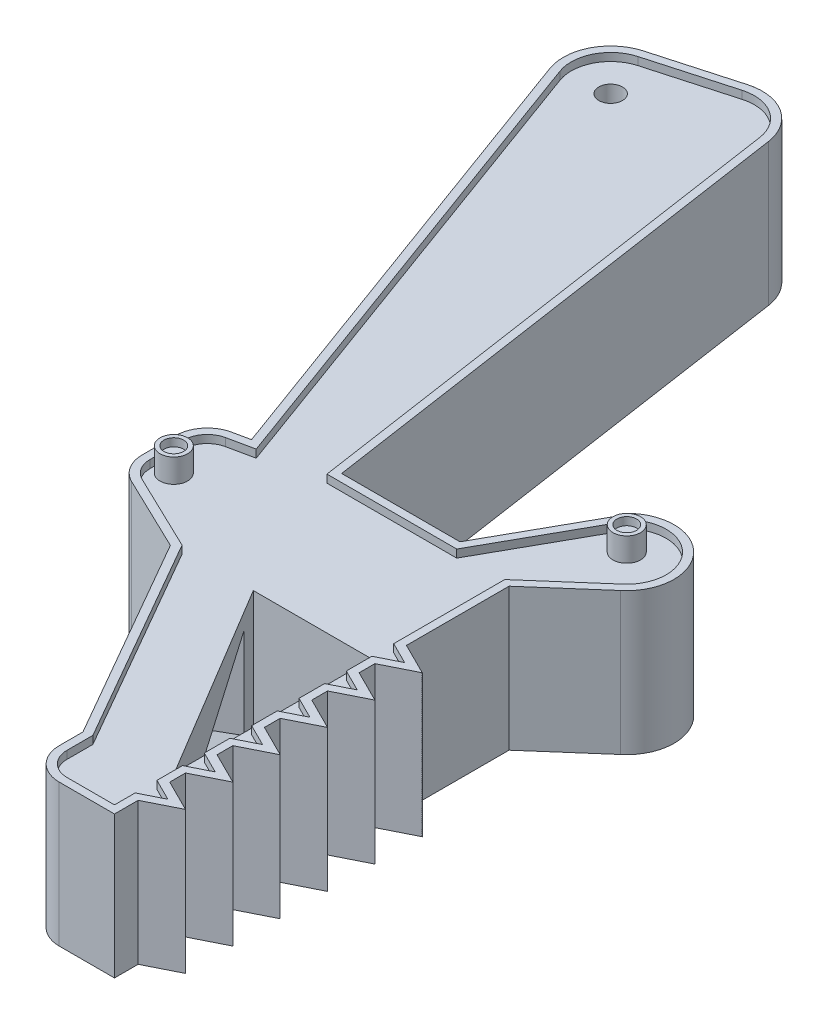
SolidWorks part; units mm, degrees
ref_plane "Front Plane" through (0, 0, 0) normal (0, 0, 1) x (1, 0, 0)
ref_plane "Top Plane" through (0, 0, 0) normal (0, 1, 0) x (1, 0, 0)
ref_plane "Right Plane" through (0, 0, 0) normal (1, 0, 0) x (0, 0, -1)
sketch "Sketch1" plane through (0, 0, 0) normal (0, 1, 0) x (1, 0, 0)
  line L0 (0, 0) -> (-94.594, 0) construction
  line L1 (-36.5878, -72.2334) -> (-60.6545, -6.5006)
  line L2 (-60.6545, -6.5006) -> (-37.5516, 0)
  line L3 (-37.5516, 0) -> (-27.1663, -70.2363)
  line L5 (-27.1663, -70.2363) -> (-41.8402, -73.3468)
  line L6 (-41.8402, -73.3468) -> (-41.8402, -83.3468)
  line L7 (-41.8402, -83.3468) -> (-30.1245, -88.9808)
  line L8 (-30.1245, -88.9808) -> (-15.1886, -114.9984)
  line L9 (-15.1886, -114.9984) -> (-15.1886, -121.9984)
  line L10 (-15.1886, -121.9984) -> (-4.1886, -121.9984)
  line L11 (-4.1886, -121.9984) -> (-4.1886, -71.9984)
  line L12 (-4.1886, -71.9984) -> (3.339, -65.4154)
  line L13 (-27.1663, -70.2363) -> (-12.169, -70.2363)
  line L14 (-12.169, -70.2363) -> (-4.3051, -56.1651)
  arc A0 (-4.3051, -56.1651) -> (3.339, -65.4154) centre (-0.483, -60.7902) cw
  dimension "D12" = 6
  dimension "D1" = 70
  dimension "D2" = 71
  dimension "D3" = 24
  dimension "D4" = 15
  dimension "D5" = 10
  dimension "D6" = 13
  dimension "D7" = 30
  dimension "D8" = 7
  dimension "D9" = 11
  dimension "D10" = 50
  dimension "D11" = 10
extrude "Boss-Extrude1" add sketch "Sketch1" along normal mid plane 18 contours L5 L3 L2 L1 | A0 L14 L13 L5 L6 L7 L8 L9 L10 L11 L12
fillet "Fillet1" radius 6 2 edges at (-37.5516, 0, 0) (-60.6545, 0, 6.5006)
fillet "Fillet2" radius 4 3 edges at (-15.1886, 0, 121.9984) (-41.8402, 0, 83.3468) (-41.8402, 0, 73.3468)
sketch "Sketch2" plane through (0, 9, 0) normal (0, 1, 0) x (1, 0, 0)
  line L0 (-4.1886, -121.9984) -> (-4.1886, -116.9984)
  line L1 (-4.1886, -121.9984) -> (-4.1886, -71.9984) construction
  line L2 (-4.1886, -116.9984) -> (-0.1886, -116.9984) construction
  line L3 (-4.1886, -114.9984) -> (-4.1886, -118.9984)
  line L4 (-4.1886, -114.9984) -> (-0.1886, -116.9984)
  line L5 (-0.1886, -116.9984) -> (-4.1886, -118.9984)
  point P9 (-4.1886, -116.9984)
  dimension "D1" = 5
  dimension "D2" = 4
  dimension "D3" = 4
extrude "Boss-Extrude2" add sketch "Sketch2" against normal blind 18 contours L4 L5 L3
pattern_linear "LPattern1" count 6 spacing 6 along (0, 0, -1) of "Boss-Extrude2"
sketch "Sketch3" plane through (0, 9, 0) normal (0, 1, 0) x (1, 0, 0)
  line L0 (-5.9101, -112.6819) -> (-5.9101, -87.6819)
  line L1 (-5.9101, -87.6819) -> (-20.9101, -87.6819)
  line L2 (-20.9101, -87.6819) -> (-5.9101, -112.6819)
  dimension "D1" = 15
  dimension "D2" = 25
extrude "Cut-Extrude1" cut sketch "Sketch3" against normal blind 26
sketch "Sketch5" plane through (-61.0774, 0, 35.0628) normal (-0.8673, 0, 0.4979) x (0.4979, 0, 0.8673)
  line L0 (68.9983, 6) -> (68.9983, -5.6071)
  line L1 (68.9983, -5.6071) -> (87.171, -0.9465)
  line L2 (87.171, -0.9465) -> (87.171, 1.3394)
  line L3 (87.171, 1.3394) -> (68.9983, 6)
  line L6 (62.171, 9) -> (92.171, 9) construction
  line L7 (92.171, 9) -> (92.171, -9) construction
  point P5 (68.9983, 0.1965)
  point P8 (87.171, 0.1965)
  dimension "D1" = 3
  dimension "D2" = 5
extrude "Cut-Extrude2" cut sketch "Sketch5" against normal blind 12
sketch "Sketch6" plane through (0, 9, 0) normal (0, 1, 0) x (1, 0, 0)
  circle A0 centre (-52.7928, -10.5215) radius 1.5
  dimension "D1" = 3
extrude "Cut-Extrude3" cut sketch "Sketch6" against normal through all
sketch "Sketch7" plane through (0, 9, 0) normal (0, 1, 0) x (1, 0, 0)
  circle A0 centre (-37.8402, -80.8319) radius 1.75
  circle A1 centre (-0.483, -60.7902) radius 1.75
  dimension "D1" = 3.5
  dimension "D2" = 3.5
extrude "Boss-Extrude3" add sketch "Sketch7" along normal blind 3
sketch "Sketch8" plane through (0, 12, 0) normal (0, 1, 0) x (1, 0, 0)
  circle A2 centre (-37.8402, -80.8319) radius 1.25
  circle A3 centre (-37.8402, -80.8319) radius 1.25
  dimension "D1" = 0.5
extrude "Cut-Extrude4" cut sketch "Sketch8" against normal blind 1
sketch "Sketch9" plane through (0, 12, 0) normal (0, 1, 0) x (1, 0, 0)
  circle A3 centre (-0.483, -60.7902) radius 1.25
  circle A4 centre (-0.483, -60.7902) radius 1.25
  dimension "D1" = 0.5
extrude "Cut-Extrude5" cut sketch "Sketch9" against normal blind 1
sketch "Sketch10" plane through (0, 9, 0) normal (0, 1, 0) x (1, 0, 0)
  line L62 (-14.1886, -114.7318) -> (-14.1886, -117.9984)
  line L63 (-11.1886, -120.9984) -> (-5.1886, -120.9984)
  line L64 (-5.1886, -120.9984) -> (-5.1886, -118.3804)
  line L65 (-5.1886, -118.3804) -> (-2.4246, -116.9984)
  line L66 (-2.4246, -116.9984) -> (-5.1886, -115.6165)
  line L67 (-5.1886, -115.6165) -> (-5.1886, -112.3804)
  line L68 (-5.1886, -112.3804) -> (-2.4246, -110.9984)
  line L69 (-2.4246, -110.9984) -> (-5.1886, -109.6165)
  line L70 (-5.1886, -109.6165) -> (-5.1886, -106.3804)
  line L71 (-5.1886, -106.3804) -> (-2.4246, -104.9984)
  line L72 (-2.4246, -104.9984) -> (-5.1886, -103.6165)
  line L73 (-5.1886, -103.6165) -> (-5.1886, -100.3804)
  line L74 (-5.1886, -100.3804) -> (-2.4246, -98.9984)
  line L75 (-2.4246, -98.9984) -> (-5.1886, -97.6165)
  line L76 (-5.1886, -97.6165) -> (-5.1886, -94.3804)
  line L77 (-5.1886, -94.3804) -> (-2.4246, -92.9984)
  line L78 (-2.4246, -92.9984) -> (-5.1886, -91.6165)
  line L79 (-5.1886, -91.6165) -> (-5.1886, -88.3804)
  line L80 (-5.1886, -88.3804) -> (-2.4246, -86.9984)
  line L81 (-2.4246, -86.9984) -> (-5.1886, -85.6165)
  line L82 (-5.1886, -85.6165) -> (-5.1886, -71.5445)
  line L83 (-5.1886, -71.5445) -> (2.6917, -64.653)
  line L84 (-3.5279, -56.8243) -> (-11.5823, -71.2363)
  line L85 (-11.5823, -71.2363) -> (-28.0293, -71.2363)
  line L86 (-28.0293, -71.2363) -> (-37.5435, -6.8911)
  line L87 (-43.8441, -2.8094) -> (-54.1471, -5.7084)
  line L88 (-57.488, -12.2406) -> (-35.2523, -72.9725)
  line L89 (-35.2523, -72.9725) -> (-38.4623, -73.653)
  line L90 (-40.8402, -76.5878) -> (-40.8402, -80.8319)
  line L91 (-39.1404, -83.5355) -> (-29.4117, -88.214)
  line L92 (-29.4117, -88.214) -> (-14.1886, -114.7318)
  line L93 (-14.1886, -114.7318) -> (-14.1886, -117.9984)
  line L94 (-11.1886, -120.9984) -> (-5.1886, -120.9984)
  line L95 (-5.1886, -120.9984) -> (-5.1886, -118.3804)
  line L96 (-5.1886, -118.3804) -> (-2.4246, -116.9984)
  line L97 (-2.4246, -116.9984) -> (-5.1886, -115.6165)
  line L98 (-5.1886, -115.6165) -> (-5.1886, -112.3804)
  line L99 (-5.1886, -112.3804) -> (-2.4246, -110.9984)
  line L100 (-2.4246, -110.9984) -> (-5.1886, -109.6165)
  line L101 (-5.1886, -109.6165) -> (-5.1886, -106.3804)
  line L102 (-5.1886, -106.3804) -> (-2.4246, -104.9984)
  line L103 (-2.4246, -104.9984) -> (-5.1886, -103.6165)
  line L104 (-5.1886, -103.6165) -> (-5.1886, -100.3804)
  line L105 (-5.1886, -100.3804) -> (-2.4246, -98.9984)
  line L106 (-2.4246, -98.9984) -> (-5.1886, -97.6165)
  line L107 (-5.1886, -97.6165) -> (-5.1886, -94.3804)
  line L108 (-5.1886, -94.3804) -> (-2.4246, -92.9984)
  line L109 (-2.4246, -92.9984) -> (-5.1886, -91.6165)
  line L110 (-5.1886, -91.6165) -> (-5.1886, -88.3804)
  line L111 (-5.1886, -88.3804) -> (-2.4246, -86.9984)
  line L112 (-2.4246, -86.9984) -> (-5.1886, -85.6165)
  line L113 (-5.1886, -85.6165) -> (-5.1886, -71.5445)
  line L114 (-5.1886, -71.5445) -> (2.6917, -64.653)
  line L115 (-3.5279, -56.8243) -> (-11.5823, -71.2363)
  line L116 (-11.5823, -71.2363) -> (-28.0293, -71.2363)
  line L117 (-28.0293, -71.2363) -> (-37.5435, -6.8911)
  line L118 (-43.8441, -2.8094) -> (-54.1471, -5.7084)
  line L119 (-57.488, -12.2406) -> (-35.2523, -72.9725)
  line L120 (-35.2523, -72.9725) -> (-38.4623, -73.653)
  line L121 (-40.8402, -76.5878) -> (-40.8402, -80.8319)
  line L122 (-39.1404, -83.5355) -> (-29.4117, -88.214)
  line L123 (-29.4117, -88.214) -> (-14.1886, -114.7318)
  arc A12 (-14.1886, -117.9984) -> (-11.1886, -120.9984) centre (-11.1886, -117.9984) ccw
  arc A13 (2.6917, -64.653) -> (-3.5279, -56.8243) centre (-0.483, -60.7902) ccw
  arc A14 (-37.5435, -6.8911) -> (-43.8441, -2.8094) centre (-42.4898, -7.6225) ccw
  arc A15 (-54.1471, -5.7084) -> (-57.488, -12.2406) centre (-52.7928, -10.5215) ccw
  arc A16 (-38.4623, -73.653) -> (-40.8402, -76.5878) centre (-37.8402, -76.5878) ccw
  arc A17 (-40.8402, -80.8319) -> (-39.1404, -83.5355) centre (-37.8402, -80.8319) ccw
  arc A18 (-14.1886, -117.9984) -> (-11.1886, -120.9984) centre (-11.1886, -117.9984) ccw
  arc A19 (2.6917, -64.653) -> (-3.5279, -56.8243) centre (-0.483, -60.7902) ccw
  arc A20 (-37.5435, -6.8911) -> (-43.8441, -2.8094) centre (-42.4898, -7.6225) ccw
  arc A21 (-54.1471, -5.7084) -> (-57.488, -12.2406) centre (-52.7928, -10.5215) ccw
  arc A22 (-38.4623, -73.653) -> (-40.8402, -76.5878) centre (-37.8402, -76.5878) ccw
  arc A23 (-40.8402, -80.8319) -> (-39.1404, -83.5355) centre (-37.8402, -80.8319) ccw
  dimension "D1" = 1
extrude "Cut-Extrude6" cut sketch "Sketch10" against normal blind 1
mirror "Mirror4" about plane through (0, 0, 0) normal (0, 1, 0) of "Cut-Extrude5", "Cut-Extrude4", "Boss-Extrude3"
sketch "Sketch12" plane through (0, -9, 0) normal (0, -1, 0) x (1, 0, 0)
  line L62 (-5.1886, 120.9984) -> (-11.1886, 120.9984)
  line L63 (-14.1886, 117.9984) -> (-14.1886, 114.7318)
  line L64 (-14.1886, 114.7318) -> (-29.4117, 88.214)
  line L65 (-29.4117, 88.214) -> (-39.1404, 83.5355)
  line L66 (-40.8402, 80.8319) -> (-40.8402, 76.5878)
  line L67 (-38.4623, 73.653) -> (-35.2523, 72.9725)
  line L68 (-35.2523, 72.9725) -> (-57.488, 12.2406)
  line L69 (-54.1471, 5.7084) -> (-43.8441, 2.8094)
  line L70 (-37.5435, 6.8911) -> (-28.0293, 71.2363)
  line L71 (-28.0293, 71.2363) -> (-11.5823, 71.2363)
  line L72 (-11.5823, 71.2363) -> (-3.5279, 56.8243)
  line L73 (2.6917, 64.653) -> (-5.1886, 71.5445)
  line L74 (-5.1886, 71.5445) -> (-5.1886, 85.6165)
  line L75 (-5.1886, 85.6165) -> (-2.4246, 86.9984)
  line L76 (-2.4246, 86.9984) -> (-5.1886, 88.3804)
  line L77 (-5.1886, 88.3804) -> (-5.1886, 91.6165)
  line L78 (-5.1886, 91.6165) -> (-2.4246, 92.9984)
  line L79 (-2.4246, 92.9984) -> (-5.1886, 94.3804)
  line L80 (-5.1886, 94.3804) -> (-5.1886, 97.6165)
  line L81 (-5.1886, 97.6165) -> (-2.4246, 98.9984)
  line L82 (-2.4246, 98.9984) -> (-5.1886, 100.3804)
  line L83 (-5.1886, 100.3804) -> (-5.1886, 103.6165)
  line L84 (-5.1886, 103.6165) -> (-2.4246, 104.9984)
  line L85 (-2.4246, 104.9984) -> (-5.1886, 106.3804)
  line L86 (-5.1886, 106.3804) -> (-5.1886, 109.6165)
  line L87 (-5.1886, 109.6165) -> (-2.4246, 110.9984)
  line L88 (-2.4246, 110.9984) -> (-5.1886, 112.3804)
  line L89 (-5.1886, 112.3804) -> (-5.1886, 115.6165)
  line L90 (-5.1886, 115.6165) -> (-2.4246, 116.9984)
  line L91 (-2.4246, 116.9984) -> (-5.1886, 118.3804)
  line L92 (-5.1886, 118.3804) -> (-5.1886, 120.9984)
  line L93 (-5.1886, 120.9984) -> (-11.1886, 120.9984)
  line L94 (-14.1886, 117.9984) -> (-14.1886, 114.7318)
  line L95 (-14.1886, 114.7318) -> (-29.4117, 88.214)
  line L96 (-29.4117, 88.214) -> (-39.1404, 83.5355)
  line L97 (-40.8402, 80.8319) -> (-40.8402, 76.5878)
  line L98 (-38.4623, 73.653) -> (-35.2523, 72.9725)
  line L99 (-35.2523, 72.9725) -> (-57.488, 12.2406)
  line L100 (-54.1471, 5.7084) -> (-43.8441, 2.8094)
  line L101 (-37.5435, 6.8911) -> (-28.0293, 71.2363)
  line L102 (-28.0293, 71.2363) -> (-11.5823, 71.2363)
  line L103 (-11.5823, 71.2363) -> (-3.5279, 56.8243)
  line L104 (2.6917, 64.653) -> (-5.1886, 71.5445)
  line L105 (-5.1886, 71.5445) -> (-5.1886, 85.6165)
  line L106 (-5.1886, 85.6165) -> (-2.4246, 86.9984)
  line L107 (-2.4246, 86.9984) -> (-5.1886, 88.3804)
  line L108 (-5.1886, 88.3804) -> (-5.1886, 91.6165)
  line L109 (-5.1886, 91.6165) -> (-2.4246, 92.9984)
  line L110 (-2.4246, 92.9984) -> (-5.1886, 94.3804)
  line L111 (-5.1886, 94.3804) -> (-5.1886, 97.6165)
  line L112 (-5.1886, 97.6165) -> (-2.4246, 98.9984)
  line L113 (-2.4246, 98.9984) -> (-5.1886, 100.3804)
  line L114 (-5.1886, 100.3804) -> (-5.1886, 103.6165)
  line L115 (-5.1886, 103.6165) -> (-2.4246, 104.9984)
  line L116 (-2.4246, 104.9984) -> (-5.1886, 106.3804)
  line L117 (-5.1886, 106.3804) -> (-5.1886, 109.6165)
  line L118 (-5.1886, 109.6165) -> (-2.4246, 110.9984)
  line L119 (-2.4246, 110.9984) -> (-5.1886, 112.3804)
  line L120 (-5.1886, 112.3804) -> (-5.1886, 115.6165)
  line L121 (-5.1886, 115.6165) -> (-2.4246, 116.9984)
  line L122 (-2.4246, 116.9984) -> (-5.1886, 118.3804)
  line L123 (-5.1886, 118.3804) -> (-5.1886, 120.9984)
  arc A12 (-11.1886, 120.9984) -> (-14.1886, 117.9984) centre (-11.1886, 117.9984) ccw
  arc A13 (-39.1404, 83.5355) -> (-40.8402, 80.8319) centre (-37.8402, 80.8319) ccw
  arc A14 (-40.8402, 76.5878) -> (-38.4623, 73.653) centre (-37.8402, 76.5878) ccw
  arc A15 (-57.488, 12.2406) -> (-54.1471, 5.7084) centre (-52.7928, 10.5215) ccw
  arc A16 (-43.8441, 2.8094) -> (-37.5435, 6.8911) centre (-42.4898, 7.6225) ccw
  arc A17 (-3.5279, 56.8243) -> (2.6917, 64.653) centre (-0.483, 60.7902) ccw
  arc A18 (-11.1886, 120.9984) -> (-14.1886, 117.9984) centre (-11.1886, 117.9984) ccw
  arc A19 (-39.1404, 83.5355) -> (-40.8402, 80.8319) centre (-37.8402, 80.8319) ccw
  arc A20 (-40.8402, 76.5878) -> (-38.4623, 73.653) centre (-37.8402, 76.5878) ccw
  arc A21 (-57.488, 12.2406) -> (-54.1471, 5.7084) centre (-52.7928, 10.5215) ccw
  arc A22 (-43.8441, 2.8094) -> (-37.5435, 6.8911) centre (-42.4898, 7.6225) ccw
  arc A23 (-3.5279, 56.8243) -> (2.6917, 64.653) centre (-0.483, 60.7902) ccw
  dimension "D1" = 1
extrude "Cut-Extrude8" cut sketch "Sketch12" against normal blind 1
